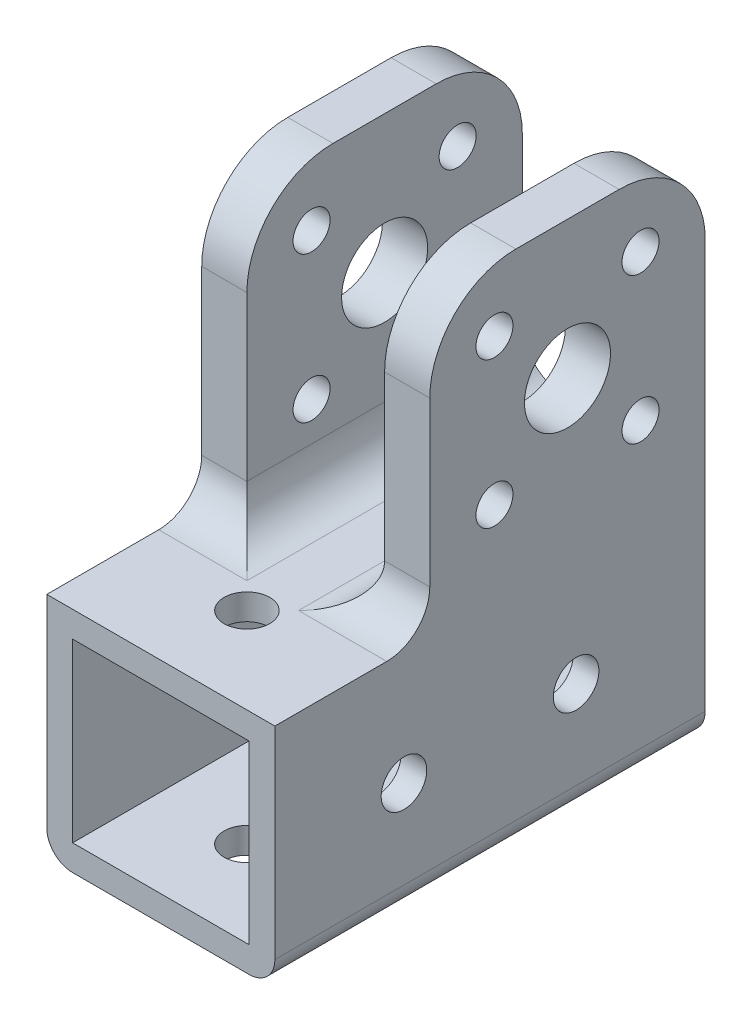
SolidWorks part; units mm, degrees
ref_plane "前视基准面" through (0, 0, 0) normal (0, 0, 1) x (1, 0, 0)
ref_plane "上视基准面" through (0, 0, 0) normal (0, 1, 0) x (1, 0, 0)
ref_plane "右视基准面" through (0, 0, 0) normal (1, 0, 0) x (0, 0, -1)
other "Configuration Table"
sketch "草图1" plane through (0, 0, 0) normal (0, 0, 1) x (1, 0, 0)
  line L0 (-13.25, 13.25) -> (13.25, 13.25)
  line L1 (-10.25, -10.25) -> (10.25, -10.25)
  line L2 (-10.25, -10.25) -> (-10.25, 10.25)
  line L3 (-10.25, 10.25) -> (10.25, 10.25)
  line L4 (10.25, -10.25) -> (10.25, 10.25)
  line L5 (-10.25, -10.25) -> (10.25, 10.25) construction
  line L6 (-10.25, 10.25) -> (10.25, -10.25) construction
  line L7 (13.25, -13.25) -> (13.25, 13.25)
  line L8 (-13.25, -13.25) -> (13.25, -13.25)
  line L9 (-13.25, -13.25) -> (-13.25, 13.25)
  point P0 (0, 0)
  dimension "D1" = 20.5
  dimension "D2" = 20.5
  dimension "D3" = 3
extrude "凸台-拉伸1" add sketch "草图1" along normal blind 50
sketch "草图2" plane through (0, 13.25, 0) normal (0, 1, 0) x (1, 0, 0)
  line L0 (-1013.25, -25) -> (48986.75, -25) construction
  line L1 (-13.25, -50) -> (-13.25, 0) construction
  line L2 (0, -1000) -> (0, 49000) construction
  line L3 (0, 0) -> (0, -32)
  line L4 (0, -32) -> (-8, -32)
  line L5 (-8, -32) -> (-8, 0)
  line L6 (13.25, 0) -> (-13.25, 0) construction
  line L7 (8, 0) -> (13.25, 0)
  line L8 (-8, 0) -> (-13.25, 0)
  line L9 (-8, 0) -> (-8, -32)
  line L10 (-8, -32) -> (-13.25, -32)
  line L11 (-13.25, 0) -> (-13.25, -32)
  line L12 (8, -32) -> (8, 0)
  line L13 (13.25, 0) -> (13.25, -32)
  line L14 (8, -32) -> (13.25, -32)
  point P6 (-13.25, -25)
  point P16 (-14.1338, -30)
  point P17 (-13.25, -30)
  point P18 (-13.25, -30)
  dimension "D1" = 32
  dimension "D2" = 8
extrude "凸台-拉伸6" add sketch "草图2" along normal blind 34 contours L10 L5 L0 L1 | L12 L14 L6 L0
sketch "草图6" plane through (-13.25, 0, 0) normal (-1, 0, 0) x (0, 0, 1)
  circle A0 centre (16, 31.25) radius 4.5
  circle A2 centre (7.5147, 39.7353) radius 2.15
  circle A3 centre (24.4853, 39.7353) radius 2.15
  circle A4 centre (24.4853, 22.7647) radius 2.15
  circle A5 centre (7.5147, 22.7647) radius 2.15
  dimension "D2" = 9
  dimension "D4" = 4.3
  dimension "D5" = 4
extrude "切除-拉伸4" cut sketch "草图6" against normal through all
fillet "圆角4" radius 5 4 edges at (10.625, 13.25, 32) (-10.625, 13.25, 32) (-8, 13.25, 16) (8, 13.25, 16)
fillet "圆角7" radius 10 2 edges at (10.625, 47.25, 0) (-10.625, 47.25, 0)
fillet "圆角8" radius 10 2 edges at (-10.625, 47.25, 32) (10.625, 47.25, 32)
fillet "圆角9" radius 3 2 edges at (-13.25, -13.25, 25) (13.25, -13.25, 25)
sketch "草图7" plane through (0, 13.25, 0) normal (0, 1, 0) x (1, 0, 0)
  line L0 (0, -50) -> (0, -40)
  line L1 (13.25, -50) -> (-13.25, -50) construction
  circle A0 centre (0, -40) radius 2.65
  dimension "D2" = 5.3
  dimension "D1" = 10
extrude "切除-拉伸5" cut sketch "草图7" against normal through all
sketch "草图8" plane through (-13.25, 0, 0) normal (-1, 0, 0) x (0, 0, 1)
  line L0 (50, -13.25) -> (50, 13.25)
  line L1 (50, 0) -> (35, 0)
  line L2 (0, 0) -> (15, 0)
  circle A0 centre (35, 0) radius 2.65
  circle A1 centre (15, 0) radius 2.65
  dimension "D2" = 5.3
  dimension "D4" = 5.3
  dimension "D1" = 15
  dimension "D3" = 15
extrude "切除-拉伸6" cut sketch "草图8" against normal through all contours A1 | A0
sketch "草图9" plane through (13.25, 0, 0) normal (1, 0, 0) x (0, 0, -1)
  circle A0 centre (-16, 31.25) radius 5
  dimension "D1" = 10
extrude "切除-拉伸7" cut sketch "草图9" against normal through all
